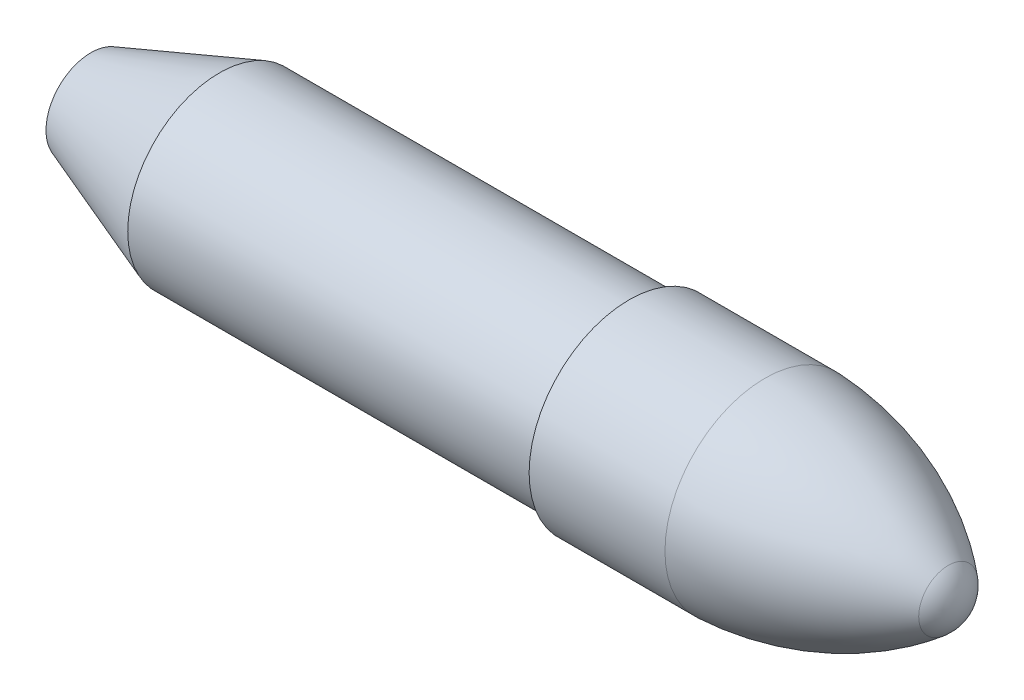
SolidWorks part; units mm, degrees
ref_plane "Plano frontal" through (0, 0, 0) normal (0, 0, 1) x (1, 0, 0)
ref_plane "Plano superior" through (0, 0, 0) normal (0, 1, 0) x (1, 0, 0)
ref_plane "Plano direito" through (0, 0, 0) normal (1, 0, 0) x (0, 0, -1)
sketch "Esboço1" plane through (0, 0, 0) normal (0, 0, 1) x (1, 0, 0)
  line L0 (0, 0) -> (34, 0) construction
  line L1 (0, 0) -> (0, 1.75)
  line L2 (0, 1.75) -> (5.0141, 3.575)
  line L3 (5.0141, 3.575) -> (21, 3.575)
  line L4 (21, 3.575) -> (21, 3.9)
  line L5 (21, 3.9) -> (26.3, 3.9)
  line L6 (0, 0) -> (34, 0)
  line L7 (34, 0) -> (34, 3.5) construction
  line L8 (34, 0) -> (35.0751, 0) construction
  arc A0 (26.3, 3.9) -> (34, 0) centre (26.3, -5.6513) cw construction
  arc A1 (26.3, 3.9) -> (33.4562, 1.1557) centre (25.8064, -8.0898) cw
  arc A2 (33.4562, 1.1557) -> (34, 0) centre (32.5, 0) cw
  dimension "D7" = 1.5
  dimension "D8" = 20
  dimension "D9" = 12
  dimension "D1" = 3.5
  dimension "D2" = 7.15
  dimension "D3" = 7.8
  dimension "D4" = 21
  dimension "D5" = 34
  dimension "D6" = 7.7
revolve "Revolução1" add sketch "Esboço1" angle 360 about L0
